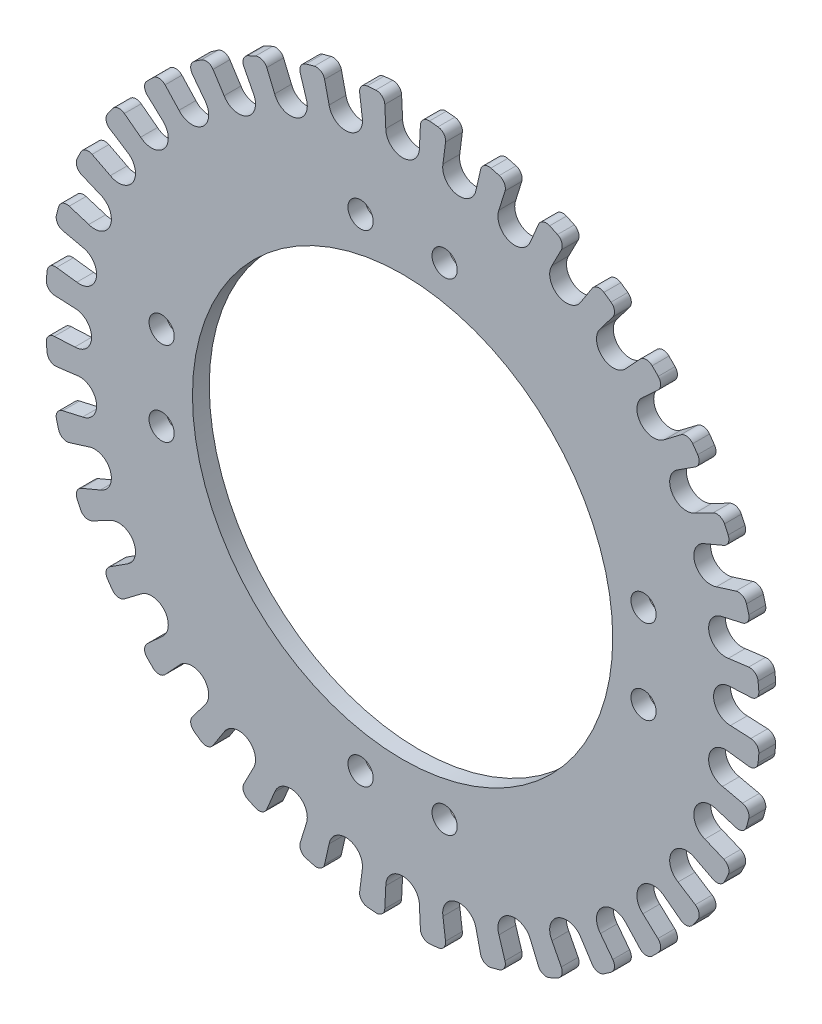
SolidWorks part; units mm, degrees
ref_plane "Front Plane" through (0, 0, 0) normal (0, 0, 1) x (1, 0, 0)
ref_plane "Top Plane" through (0, 0, 0) normal (0, 1, 0) x (1, 0, 0)
ref_plane "Right Plane" through (0, 0, 0) normal (1, 0, 0) x (0, 0, -1)
sketch "Sketch1" plane through (0, 0, 0) normal (0, 0, 1) x (1, 0, 0)
  line L0 (5.1087, 41.1696) -> (4.8027, 38.7548)
  line L1 (2, 39) -> (2.118, 41.4313)
  line L2 (-2.118, 41.4313) -> (-2, 39)
  line L3 (-4.8027, 38.7548) -> (-5.1087, 41.1696)
  line L4 (-9.2803, 40.434) -> (-8.7419, 38.0602)
  line L5 (-11.4594, 37.3321) -> (-12.1801, 39.657)
  line L6 (-16.1606, 38.2083) -> (-15.2182, 35.964)
  line L7 (-17.7679, 34.775) -> (-18.8814, 36.9395)
  line L8 (-22.5499, 34.8215) -> (-21.2321, 32.775)
  line L9 (-23.5366, 31.1613) -> (-25.009, 33.0996)
  line L10 (-28.254, 30.3768) -> (-26.6008, 28.5902)
  line L11 (-28.5902, 26.6008) -> (-30.3768, 28.254)
  line L12 (-33.0996, 25.009) -> (-31.1613, 23.5366)
  line L13 (-32.775, 21.2321) -> (-34.8215, 22.5499)
  line L14 (-36.9395, 18.8814) -> (-34.775, 17.7679)
  line L15 (-35.964, 15.2182) -> (-38.2083, 16.1606)
  line L16 (-39.657, 12.1801) -> (-37.3321, 11.4594)
  line L17 (-38.0602, 8.7419) -> (-40.434, 9.2803)
  line L18 (-41.1696, 5.1087) -> (-38.7548, 4.8027)
  line L19 (-39, 2) -> (-41.4313, 2.118)
  line L20 (-41.4313, -2.118) -> (-39, -2)
  line L21 (-38.7548, -4.8027) -> (-41.1696, -5.1087)
  line L22 (-40.434, -9.2803) -> (-38.0602, -8.7419)
  line L23 (-37.3321, -11.4594) -> (-39.657, -12.1801)
  line L24 (-38.2083, -16.1606) -> (-35.964, -15.2182)
  line L25 (-34.775, -17.7679) -> (-36.9395, -18.8814)
  line L26 (-34.8215, -22.5499) -> (-32.775, -21.2321)
  line L27 (-31.1613, -23.5366) -> (-33.0996, -25.009)
  line L28 (-30.3768, -28.254) -> (-28.5902, -26.6008)
  line L29 (-26.6008, -28.5902) -> (-28.254, -30.3768)
  line L30 (-25.009, -33.0996) -> (-23.5366, -31.1613)
  line L31 (-21.2321, -32.775) -> (-22.5499, -34.8215)
  line L32 (-18.8814, -36.9395) -> (-17.7679, -34.775)
  line L33 (-15.2182, -35.964) -> (-16.1606, -38.2083)
  line L34 (-12.1801, -39.657) -> (-11.4594, -37.3321)
  line L35 (-8.7419, -38.0602) -> (-9.2803, -40.434)
  line L36 (-5.1087, -41.1696) -> (-4.8027, -38.7548)
  line L37 (-2, -39) -> (-2.118, -41.4313)
  line L38 (2.118, -41.4313) -> (2, -39)
  line L39 (4.8027, -38.7548) -> (5.1087, -41.1696)
  line L40 (9.2803, -40.434) -> (8.7419, -38.0602)
  line L41 (11.4594, -37.3321) -> (12.1801, -39.657)
  line L42 (16.1606, -38.2083) -> (15.2182, -35.964)
  line L43 (17.7679, -34.775) -> (18.8814, -36.9395)
  line L44 (22.5499, -34.8215) -> (21.2321, -32.775)
  line L45 (23.5366, -31.1613) -> (25.009, -33.0996)
  line L46 (28.254, -30.3768) -> (26.6008, -28.5902)
  line L47 (28.5902, -26.6008) -> (30.3768, -28.254)
  line L48 (33.0996, -25.009) -> (31.1613, -23.5366)
  line L49 (32.775, -21.2321) -> (34.8215, -22.5499)
  line L50 (36.9395, -18.8814) -> (34.775, -17.7679)
  line L51 (35.964, -15.2182) -> (38.2083, -16.1606)
  line L52 (39.657, -12.1801) -> (37.3321, -11.4594)
  line L53 (38.0602, -8.7419) -> (40.434, -9.2803)
  line L54 (41.1696, -5.1087) -> (38.7548, -4.8027)
  line L55 (39, -2) -> (41.4313, -2.118)
  line L56 (41.4313, 2.118) -> (39, 2)
  line L57 (38.7548, 4.8027) -> (41.1696, 5.1087)
  line L58 (40.434, 9.2803) -> (38.0602, 8.7419)
  line L59 (37.3321, 11.4594) -> (39.657, 12.1801)
  line L60 (38.2083, 16.1606) -> (35.964, 15.2182)
  line L61 (34.775, 17.7679) -> (36.9395, 18.8814)
  line L62 (34.8215, 22.5499) -> (32.775, 21.2321)
  line L63 (31.1613, 23.5366) -> (33.0996, 25.009)
  line L64 (30.3768, 28.254) -> (28.5902, 26.6008)
  line L65 (26.6008, 28.5902) -> (28.254, 30.3768)
  line L66 (25.009, 33.0996) -> (23.5366, 31.1613)
  line L67 (21.2321, 32.775) -> (22.5499, 34.8215)
  line L68 (18.8814, 36.9395) -> (17.7679, 34.775)
  line L69 (15.2182, 35.964) -> (16.1606, 38.2083)
  line L70 (12.1801, 39.657) -> (11.4594, 37.3321)
  line L71 (8.7419, 38.0602) -> (9.2803, 40.434)
  arc A0 (5.1087, 41.1696) -> (4.2158, 42.2904) centre (4.1166, 41.2953) ccw
  arc A1 (4.2158, 42.2904) -> (3.1919, 42.38) centre (0, 0) ccw
  arc A2 (3.1919, 42.38) -> (2.118, 41.4313) centre (3.1168, 41.3828) ccw
  arc A3 (-2, 39) -> (2, 39) centre (0, 39) ccw
  arc A4 (-2.118, 41.4313) -> (-3.1919, 42.38) centre (-3.1168, 41.3828) ccw
  arc A5 (-3.1919, 42.38) -> (-4.2158, 42.2904) centre (0, 0) ccw
  arc A6 (-4.2158, 42.2904) -> (-5.1087, 41.1696) centre (-4.1166, 41.2953) ccw
  arc A7 (-8.7419, 38.0602) -> (-4.8027, 38.7548) centre (-6.7723, 38.4075) ccw
  arc A8 (-9.2803, 40.434) -> (-10.5026, 41.1819) centre (-10.2555, 40.2129) ccw
  arc A9 (-10.5026, 41.1819) -> (-11.4954, 40.9158) centre (0, 0) ccw
  arc A10 (-11.4954, 40.9158) -> (-12.1801, 39.657) centre (-11.2249, 39.9531) ccw
  arc A11 (-15.2182, 35.964) -> (-11.4594, 37.3321) centre (-13.3388, 36.648) ccw
  arc A12 (-16.1606, 38.2083) -> (-17.4942, 38.7324) centre (-17.0826, 37.8211) ccw
  arc A13 (-17.4942, 38.7324) -> (-18.4257, 38.2981) centre (0, 0) ccw
  arc A14 (-18.4257, 38.2981) -> (-18.8814, 36.9395) centre (-17.9922, 37.397) ccw
  arc A15 (-21.2321, 32.775) -> (-17.7679, 34.775) centre (-19.5, 33.775) ccw
  arc A16 (-22.5499, 34.8215) -> (-23.9543, 35.1062) centre (-23.3906, 34.2801) ccw
  arc A17 (-23.9543, 35.1062) -> (-24.7962, 34.5167) centre (0, 0) ccw
  arc A18 (-24.7962, 34.5167) -> (-25.009, 33.0996) centre (-24.2127, 33.7045) ccw
  arc A19 (-26.6008, 28.5902) -> (-23.5366, 31.1613) centre (-25.0687, 29.8757) ccw
  arc A20 (-28.254, 30.3768) -> (-29.6865, 30.4132) centre (-28.988, 29.6976) ccw
  arc A21 (-29.6865, 30.4132) -> (-30.4132, 29.6865) centre (0, 0) ccw
  arc A22 (-30.4132, 29.6865) -> (-30.3768, 28.254) centre (-29.6976, 28.988) ccw
  arc A23 (-31.1613, 23.5366) -> (-28.5902, 26.6008) centre (-29.8757, 25.0687) ccw
  arc A24 (-33.0996, 25.009) -> (-34.5167, 24.7962) centre (-33.7045, 24.2127) ccw
  arc A25 (-34.5167, 24.7962) -> (-35.1062, 23.9543) centre (0, 0) ccw
  arc A26 (-35.1062, 23.9543) -> (-34.8215, 22.5499) centre (-34.2801, 23.3906) ccw
  arc A27 (-34.775, 17.7679) -> (-32.775, 21.2321) centre (-33.775, 19.5) ccw
  arc A28 (-36.9395, 18.8814) -> (-38.2981, 18.4257) centre (-37.397, 17.9922) ccw
  arc A29 (-38.2981, 18.4257) -> (-38.7324, 17.4942) centre (0, 0) ccw
  arc A30 (-38.7324, 17.4942) -> (-38.2083, 16.1606) centre (-37.8211, 17.0826) ccw
  arc A31 (-37.3321, 11.4594) -> (-35.964, 15.2182) centre (-36.648, 13.3388) ccw
  arc A32 (-39.657, 12.1801) -> (-40.9158, 11.4954) centre (-39.9531, 11.2249) ccw
  arc A33 (-40.9158, 11.4954) -> (-41.1819, 10.5026) centre (0, 0) ccw
  arc A34 (-41.1819, 10.5026) -> (-40.434, 9.2803) centre (-40.2129, 10.2555) ccw
  arc A35 (-38.7548, 4.8027) -> (-38.0602, 8.7419) centre (-38.4075, 6.7723) ccw
  arc A36 (-41.1696, 5.1087) -> (-42.2904, 4.2158) centre (-41.2953, 4.1166) ccw
  arc A37 (-42.2904, 4.2158) -> (-42.38, 3.1919) centre (0, 0) ccw
  arc A38 (-42.38, 3.1919) -> (-41.4313, 2.118) centre (-41.3828, 3.1168) ccw
  arc A39 (-39, -2) -> (-39, 2) centre (-39, 0) ccw
  arc A40 (-41.4313, -2.118) -> (-42.38, -3.1919) centre (-41.3828, -3.1168) ccw
  arc A41 (-42.38, -3.1919) -> (-42.2904, -4.2158) centre (0, 0) ccw
  arc A42 (-42.2904, -4.2158) -> (-41.1696, -5.1087) centre (-41.2953, -4.1166) ccw
  arc A43 (-38.0602, -8.7419) -> (-38.7548, -4.8027) centre (-38.4075, -6.7723) ccw
  arc A44 (-40.434, -9.2803) -> (-41.1819, -10.5026) centre (-40.2129, -10.2555) ccw
  arc A45 (-41.1819, -10.5026) -> (-40.9158, -11.4954) centre (0, 0) ccw
  arc A46 (-40.9158, -11.4954) -> (-39.657, -12.1801) centre (-39.9531, -11.2249) ccw
  arc A47 (-35.964, -15.2182) -> (-37.3321, -11.4594) centre (-36.648, -13.3388) ccw
  arc A48 (-38.2083, -16.1606) -> (-38.7324, -17.4942) centre (-37.8211, -17.0826) ccw
  arc A49 (-38.7324, -17.4942) -> (-38.2981, -18.4257) centre (0, 0) ccw
  arc A50 (-38.2981, -18.4257) -> (-36.9395, -18.8814) centre (-37.397, -17.9922) ccw
  arc A51 (-32.775, -21.2321) -> (-34.775, -17.7679) centre (-33.775, -19.5) ccw
  arc A52 (-34.8215, -22.5499) -> (-35.1062, -23.9543) centre (-34.2801, -23.3906) ccw
  arc A53 (-35.1062, -23.9543) -> (-34.5167, -24.7962) centre (0, 0) ccw
  arc A54 (-34.5167, -24.7962) -> (-33.0996, -25.009) centre (-33.7045, -24.2127) ccw
  arc A55 (-28.5902, -26.6008) -> (-31.1613, -23.5366) centre (-29.8757, -25.0687) ccw
  arc A56 (-30.3768, -28.254) -> (-30.4132, -29.6865) centre (-29.6976, -28.988) ccw
  arc A57 (-30.4132, -29.6865) -> (-29.6865, -30.4132) centre (0, 0) ccw
  arc A58 (-29.6865, -30.4132) -> (-28.254, -30.3768) centre (-28.988, -29.6976) ccw
  arc A59 (-23.5366, -31.1613) -> (-26.6008, -28.5902) centre (-25.0687, -29.8757) ccw
  arc A60 (-25.009, -33.0996) -> (-24.7962, -34.5167) centre (-24.2127, -33.7045) ccw
  arc A61 (-24.7962, -34.5167) -> (-23.9543, -35.1062) centre (0, 0) ccw
  arc A62 (-23.9543, -35.1062) -> (-22.5499, -34.8215) centre (-23.3906, -34.2801) ccw
  arc A63 (-17.7679, -34.775) -> (-21.2321, -32.775) centre (-19.5, -33.775) ccw
  arc A64 (-18.8814, -36.9395) -> (-18.4257, -38.2981) centre (-17.9922, -37.397) ccw
  arc A65 (-18.4257, -38.2981) -> (-17.4942, -38.7324) centre (0, 0) ccw
  arc A66 (-17.4942, -38.7324) -> (-16.1606, -38.2083) centre (-17.0826, -37.8211) ccw
  arc A67 (-11.4594, -37.3321) -> (-15.2182, -35.964) centre (-13.3388, -36.648) ccw
  arc A68 (-12.1801, -39.657) -> (-11.4954, -40.9158) centre (-11.2249, -39.9531) ccw
  arc A69 (-11.4954, -40.9158) -> (-10.5026, -41.1819) centre (0, 0) ccw
  arc A70 (-10.5026, -41.1819) -> (-9.2803, -40.434) centre (-10.2555, -40.2129) ccw
  arc A71 (-4.8027, -38.7548) -> (-8.7419, -38.0602) centre (-6.7723, -38.4075) ccw
  arc A72 (-5.1087, -41.1696) -> (-4.2158, -42.2904) centre (-4.1166, -41.2953) ccw
  arc A73 (-4.2158, -42.2904) -> (-3.1919, -42.38) centre (0, 0) ccw
  arc A74 (-3.1919, -42.38) -> (-2.118, -41.4313) centre (-3.1168, -41.3828) ccw
  arc A75 (2, -39) -> (-2, -39) centre (0, -39) ccw
  arc A76 (2.118, -41.4313) -> (3.1919, -42.38) centre (3.1168, -41.3828) ccw
  arc A77 (3.1919, -42.38) -> (4.2158, -42.2904) centre (0, 0) ccw
  arc A78 (4.2158, -42.2904) -> (5.1087, -41.1696) centre (4.1166, -41.2953) ccw
  arc A79 (8.7419, -38.0602) -> (4.8027, -38.7548) centre (6.7723, -38.4075) ccw
  arc A80 (9.2803, -40.434) -> (10.5026, -41.1819) centre (10.2555, -40.2129) ccw
  arc A81 (10.5026, -41.1819) -> (11.4954, -40.9158) centre (0, 0) ccw
  arc A82 (11.4954, -40.9158) -> (12.1801, -39.657) centre (11.2249, -39.9531) ccw
  arc A83 (15.2182, -35.964) -> (11.4594, -37.3321) centre (13.3388, -36.648) ccw
  arc A84 (16.1606, -38.2083) -> (17.4942, -38.7324) centre (17.0826, -37.8211) ccw
  arc A85 (17.4942, -38.7324) -> (18.4257, -38.2981) centre (0, 0) ccw
  arc A86 (18.4257, -38.2981) -> (18.8814, -36.9395) centre (17.9922, -37.397) ccw
  arc A87 (21.2321, -32.775) -> (17.7679, -34.775) centre (19.5, -33.775) ccw
  arc A88 (22.5499, -34.8215) -> (23.9543, -35.1062) centre (23.3906, -34.2801) ccw
  arc A89 (23.9543, -35.1062) -> (24.7962, -34.5167) centre (0, 0) ccw
  arc A90 (24.7962, -34.5167) -> (25.009, -33.0996) centre (24.2127, -33.7045) ccw
  arc A91 (26.6008, -28.5902) -> (23.5366, -31.1613) centre (25.0687, -29.8757) ccw
  arc A92 (28.254, -30.3768) -> (29.6865, -30.4132) centre (28.988, -29.6976) ccw
  arc A93 (29.6865, -30.4132) -> (30.4132, -29.6865) centre (0, 0) ccw
  arc A94 (30.4132, -29.6865) -> (30.3768, -28.254) centre (29.6976, -28.988) ccw
  arc A95 (31.1613, -23.5366) -> (28.5902, -26.6008) centre (29.8757, -25.0687) ccw
  arc A96 (33.0996, -25.009) -> (34.5167, -24.7962) centre (33.7045, -24.2127) ccw
  arc A97 (34.5167, -24.7962) -> (35.1062, -23.9543) centre (0, 0) ccw
  arc A98 (35.1062, -23.9543) -> (34.8215, -22.5499) centre (34.2801, -23.3906) ccw
  arc A99 (34.775, -17.7679) -> (32.775, -21.2321) centre (33.775, -19.5) ccw
  arc A100 (36.9395, -18.8814) -> (38.2981, -18.4257) centre (37.397, -17.9922) ccw
  arc A101 (38.2981, -18.4257) -> (38.7324, -17.4942) centre (0, 0) ccw
  arc A102 (38.7324, -17.4942) -> (38.2083, -16.1606) centre (37.8211, -17.0826) ccw
  arc A103 (37.3321, -11.4594) -> (35.964, -15.2182) centre (36.648, -13.3388) ccw
  arc A104 (39.657, -12.1801) -> (40.9158, -11.4954) centre (39.9531, -11.2249) ccw
  arc A105 (40.9158, -11.4954) -> (41.1819, -10.5026) centre (0, 0) ccw
  arc A106 (41.1819, -10.5026) -> (40.434, -9.2803) centre (40.2129, -10.2555) ccw
  arc A107 (38.7548, -4.8027) -> (38.0602, -8.7419) centre (38.4075, -6.7723) ccw
  arc A108 (41.1696, -5.1087) -> (42.2904, -4.2158) centre (41.2953, -4.1166) ccw
  arc A109 (42.2904, -4.2158) -> (42.38, -3.1919) centre (0, 0) ccw
  arc A110 (42.38, -3.1919) -> (41.4313, -2.118) centre (41.3828, -3.1168) ccw
  arc A111 (39, 2) -> (39, -2) centre (39, 0) ccw
  arc A112 (41.4313, 2.118) -> (42.38, 3.1919) centre (41.3828, 3.1168) ccw
  arc A113 (42.38, 3.1919) -> (42.2904, 4.2158) centre (0, 0) ccw
  arc A114 (42.2904, 4.2158) -> (41.1696, 5.1087) centre (41.2953, 4.1166) ccw
  arc A115 (38.0602, 8.7419) -> (38.7548, 4.8027) centre (38.4075, 6.7723) ccw
  arc A116 (40.434, 9.2803) -> (41.1819, 10.5026) centre (40.2129, 10.2555) ccw
  arc A117 (41.1819, 10.5026) -> (40.9158, 11.4954) centre (0, 0) ccw
  arc A118 (40.9158, 11.4954) -> (39.657, 12.1801) centre (39.9531, 11.2249) ccw
  arc A119 (35.964, 15.2182) -> (37.3321, 11.4594) centre (36.648, 13.3388) ccw
  arc A120 (38.2083, 16.1606) -> (38.7324, 17.4942) centre (37.8211, 17.0826) ccw
  arc A121 (38.7324, 17.4942) -> (38.2981, 18.4257) centre (0, 0) ccw
  arc A122 (38.2981, 18.4257) -> (36.9395, 18.8814) centre (37.397, 17.9922) ccw
  arc A123 (32.775, 21.2321) -> (34.775, 17.7679) centre (33.775, 19.5) ccw
  arc A124 (34.8215, 22.5499) -> (35.1062, 23.9543) centre (34.2801, 23.3906) ccw
  arc A125 (35.1062, 23.9543) -> (34.5167, 24.7962) centre (0, 0) ccw
  arc A126 (34.5167, 24.7962) -> (33.0996, 25.009) centre (33.7045, 24.2127) ccw
  arc A127 (28.5902, 26.6008) -> (31.1613, 23.5366) centre (29.8757, 25.0687) ccw
  arc A128 (30.3768, 28.254) -> (30.4132, 29.6865) centre (29.6976, 28.988) ccw
  arc A129 (30.4132, 29.6865) -> (29.6865, 30.4132) centre (0, 0) ccw
  arc A130 (29.6865, 30.4132) -> (28.254, 30.3768) centre (28.988, 29.6976) ccw
  arc A131 (23.5366, 31.1613) -> (26.6008, 28.5902) centre (25.0687, 29.8757) ccw
  arc A132 (25.009, 33.0996) -> (24.7962, 34.5167) centre (24.2127, 33.7045) ccw
  arc A133 (24.7962, 34.5167) -> (23.9543, 35.1062) centre (0, 0) ccw
  arc A134 (23.9543, 35.1062) -> (22.5499, 34.8215) centre (23.3906, 34.2801) ccw
  arc A135 (17.7679, 34.775) -> (21.2321, 32.775) centre (19.5, 33.775) ccw
  arc A136 (18.8814, 36.9395) -> (18.4257, 38.2981) centre (17.9922, 37.397) ccw
  arc A137 (18.4257, 38.2981) -> (17.4942, 38.7324) centre (0, 0) ccw
  arc A138 (17.4942, 38.7324) -> (16.1606, 38.2083) centre (17.0826, 37.8211) ccw
  arc A139 (11.4594, 37.3321) -> (15.2182, 35.964) centre (13.3388, 36.648) ccw
  arc A140 (12.1801, 39.657) -> (11.4954, 40.9158) centre (11.2249, 39.9531) ccw
  arc A141 (11.4954, 40.9158) -> (10.5026, 41.1819) centre (0, 0) ccw
  arc A142 (10.5026, 41.1819) -> (9.2803, 40.434) centre (10.2555, 40.2129) ccw
  arc A143 (4.8027, 38.7548) -> (8.7419, 38.0602) centre (6.7723, 38.4075) ccw
  circle A144 centre (-28.6654, -5) radius 1.5
  circle A145 centre (5, -28.6654) radius 1.5
  circle A146 centre (28.6654, 5) radius 1.5
  circle A147 centre (-5, 28.6654) radius 1.5
  circle A148 centre (0, 0) radius 25
  circle A149 centre (5, 28.6654) radius 1.5
  circle A150 centre (28.6654, -5) radius 1.5
  circle A151 centre (-5, -28.6654) radius 1.5
  circle A152 centre (-28.6654, 5) radius 1.5
extrude "Boss-Extrude1" add sketch "Sketch1" along normal blind 2
